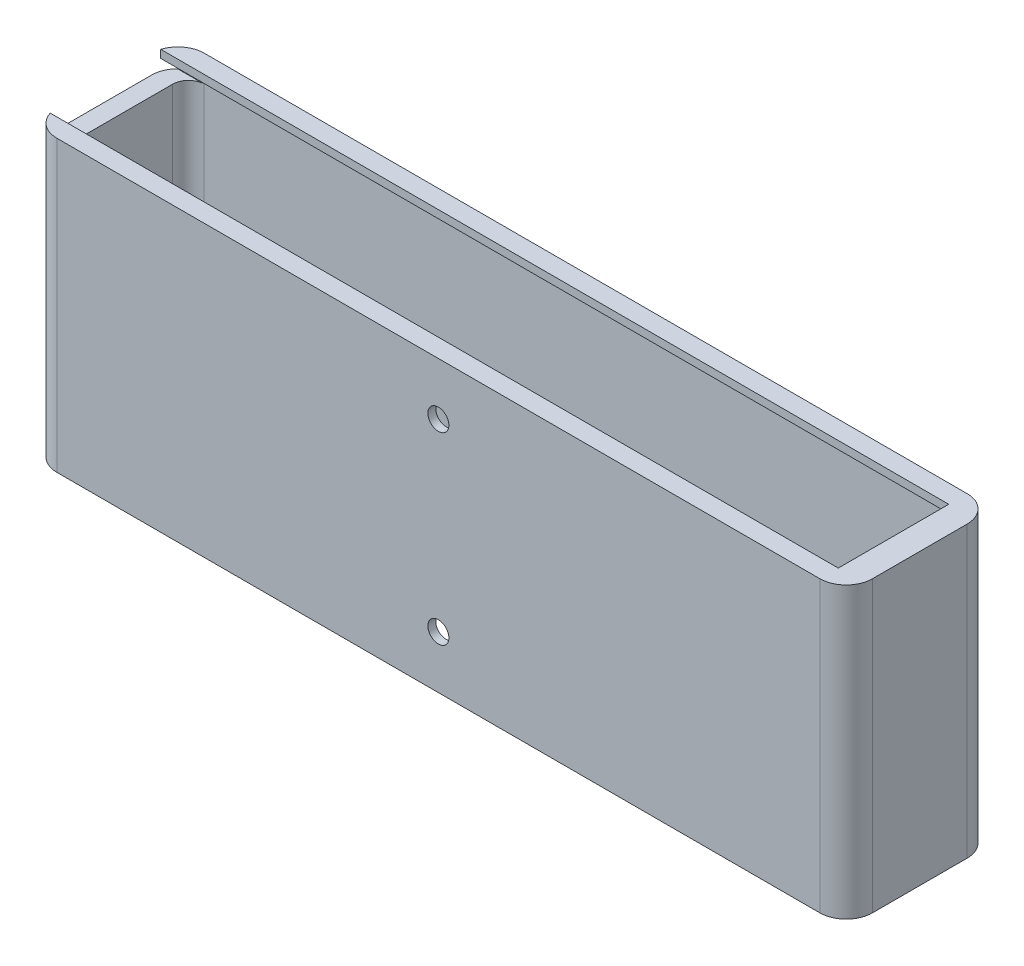
SolidWorks part; units mm, degrees
material "PVC 0.007 Plasticizado"
ref_plane "Plano frontal" through (0, 0, 0) normal (0, 0, 1) x (1, 0, 0)
ref_plane "Plano superior" through (0, 0, 0) normal (0, 1, 0) x (1, 0, 0)
ref_plane "Plano direito" through (0, 0, 0) normal (1, 0, 0) x (0, 0, -1)
sketch "Esboço1" plane through (0, 0, 0) normal (0, 0, 1) x (1, 0, 0)
  line L1 (-77.5, -27.5) -> (77.5, -27.5)
  line L2 (-77.5, -27.5) -> (-77.5, 27.5)
  line L3 (-77.5, 27.5) -> (77.5, 27.5)
  line L4 (77.5, -27.5) -> (77.5, 27.5)
  line L5 (-77.5, -27.5) -> (77.5, 27.5) construction
  line L6 (-77.5, 27.5) -> (77.5, -27.5) construction
  point P0 (0, 0)
  dimension "D1" = 55
  dimension "D2" = 155
extrude "Ressalto-extrusão1" add sketch "Esboço1" along normal blind 28
sketch "Esboço3" plane through (0, -27.5, 0) normal (0, -1, 0) x (1, 0, 0)
  line L0 (0, 0) -> (0, 28) construction
  line L1 (-77.5, 0) -> (77.5, 0) construction
  line L2 (-77.5, 28) -> (77.5, 28) construction
  line L4 (-74, 1.5) -> (74, 1.5)
  line L5 (-74, 1.5) -> (-74, 26.5)
  line L6 (-74, 26.5) -> (74, 26.5)
  line L7 (74, 1.5) -> (74, 26.5)
  line L8 (-74, 1.5) -> (74, 26.5) construction
  line L9 (-74, 26.5) -> (74, 1.5) construction
  point P6 (0, 14)
  dimension "D1" = 148
  dimension "D2" = 25
extrude "Corte-extrusão1" cut sketch "Esboço3" against normal through all
sketch "Esboço4" plane through (-77.5, 0, 0) normal (-1, 0, 0) x (0, 0, 1)
  line L0 (3.5, 27.5) -> (3.5, 26)
  line L2 (24.5, 27.5) -> (24.5, 26)
  line L3 (24.5, 26) -> (26.5, 26)
  line L4 (28, 27.5) -> (0, 27.5) construction
  line L5 (3.5, 26) -> (1.5, 26)
  line L6 (1.5, 26) -> (1.5, 23.9)
  line L7 (1.5, 23.9) -> (26.5, 23.9)
  line L8 (14, 23.9) -> (14, 27.5) construction
  line L9 (3.5, 27.5) -> (24.5, 27.5)
  line L10 (26.5, 26) -> (26.5, 23.9)
  dimension "D1" = 1.5
  dimension "D2" = 2.1
  dimension "D3" = 12.5
  dimension "D4" = 10.5
extrude "Corte-extrusão2" cut sketch "Esboço4" against normal up to next
sketch "Esboço6" plane through (-74, 0, 0) normal (1, 0, 0) x (0, 0, -1)
  line L0 (-3.5, 27.5) -> (-1.5, 27.5)
  line L1 (-1.5, 27.5) -> (-1.5, 26)
  line L2 (-1.5, 26) -> (-3.5, 26)
  line L3 (-3.5, 26) -> (-3.5, 27.5)
extrude "Ressalto-extrusão2" add sketch "Esboço6" along normal up to next
sketch "Esboço7" plane through (-74, 0, 0) normal (1, 0, 0) x (0, 0, -1)
  line L0 (-26.5, 27.5) -> (-24.5, 27.5)
  line L1 (-24.5, 27.5) -> (-24.5, 26)
  line L2 (-24.5, 26) -> (-26.5, 26)
  line L3 (-26.5, 26) -> (-26.5, 27.5)
extrude "Ressalto-extrusão3" add sketch "Esboço7" along normal up to next
sketch "Esboço9" plane through (74, 0, 0) normal (-1, 0, 0) x (0, 0, 1)
  line L0 (24.5, 27.5) -> (24.5, 26)
  line L1 (24.5, 26) -> (3.5, 26)
  line L2 (3.5, 26) -> (3.5, 27.5)
  line L3 (3.5, 27.5) -> (24.5, 27.5)
extrude "Ressalto-extrusão4" add sketch "Esboço9" along normal blind 1.5
fillet "Filete1" radius 5 4 edges at (-77.5, 0, 28) (-77.5, 0, 0) (77.5, 0, 0) (77.5, 0, 28)
fillet "Filete2" radius 3 4 edges at (-74, -1.8, 1.5) (-74, -1.8, 26.5) (74, -0.75, 26.5) (74, -0.75, 1.5)
sketch "Esboço12" plane through (0, -27.5, 0) normal (0, -1, 0) x (1, 0, 0)
  line L0 (74, 4.5) -> (74, 23.5) construction
  line L1 (-44.2797, 26.5) -> (-44.2797, 1.5) construction
  line L2 (74, 14) -> (-77.5, 14) construction
  line L3 (-77.5, 23) -> (-77.5, 5) construction
  line L4 (-21.3047, 26.5) -> (-17.5594, 26.5)
  line L5 (71, 26.5) -> (-76.0707, 26.5) construction
  line L7 (-71, 1.5) -> (71, 1.5) construction
  line L8 (-29.4196, 16.3438) -> (-21.3047, 26.5)
  line L11 (-29.4196, 16.3438) -> (-37.5344, 26.5)
  line L13 (-37.5344, 26.5) -> (-41.2797, 26.5)
  line L18 (-41.2797, 26.5) -> (-31.2922, 14)
  line L25 (-71, 26.5) -> (-71, 1.5) construction
  line L26 (-71, 26.5) -> (-61.0125, 14)
  line L27 (-41.2797, 1.5) -> (-31.2922, 14)
  line L28 (71, 1.5) -> (-76.0707, 1.5) construction
  line L29 (-51.025, 1.5) -> (-47.2797, 1.5)
  line L30 (-47.2797, 1.5) -> (-57.2672, 14)
  line L31 (71, 26.5) -> (-71, 26.5) construction
  line L32 (-67.2547, 26.5) -> (-71, 26.5)
  line L33 (-71, 1.5) -> (-61.0125, 14)
  line L34 (-51.025, 26.5) -> (-47.2797, 26.5)
  line L35 (-47.2797, 26.5) -> (-57.2672, 14)
  line L36 (-67.2547, 1.5) -> (-71, 1.5)
  line L37 (-59.1399, 16.3437) -> (-51.025, 26.5)
  line L38 (-59.1399, 16.3437) -> (-67.2547, 26.5)
  line L39 (-59.1399, 11.6562) -> (-67.2547, 1.5)
  line L40 (-59.1399, 11.6562) -> (-51.025, 1.5)
  line L41 (-37.5344, 1.5) -> (-41.2797, 1.5)
  line L42 (-29.4196, 11.6562) -> (-37.5344, 1.5)
  line L43 (-29.4196, 11.6562) -> (-21.3047, 1.5)
  line L44 (-21.3047, 1.5) -> (-17.5594, 1.5)
  line L45 (-17.5594, 1.5) -> (-27.5469, 14)
  line L46 (-17.5594, 26.5) -> (-27.5469, 14)
  line L47 (-14.5594, 26.5) -> (-14.5594, 1.5) construction
  line L48 (0.3007, 16.3438) -> (-7.8141, 26.5)
  line L49 (0.3007, 16.3438) -> (8.4156, 26.5)
  line L50 (8.4156, 26.5) -> (12.1609, 26.5)
  line L51 (12.1609, 26.5) -> (2.1734, 14)
  line L52 (12.1609, 1.5) -> (2.1734, 14)
  line L53 (8.4156, 1.5) -> (12.1609, 1.5)
  line L54 (0.3007, 11.6562) -> (8.4156, 1.5)
  line L55 (0.3007, 11.6562) -> (-7.8141, 1.5)
  line L56 (-7.8141, 1.5) -> (-11.5594, 1.5)
  line L57 (-11.5594, 1.5) -> (-1.5719, 14)
  line L58 (-11.5594, 26.5) -> (-1.5719, 14)
  line L59 (-7.8141, 26.5) -> (-11.5594, 26.5)
  line L60 (15.1609, 26.5) -> (15.1609, 1.5) construction
  line L61 (30.021, 16.3438) -> (21.9062, 26.5)
  line L62 (21.9062, 26.5) -> (18.1609, 26.5)
  line L63 (18.1609, 26.5) -> (28.1484, 14)
  line L64 (18.1609, 1.5) -> (28.1484, 14)
  line L65 (21.9062, 1.5) -> (18.1609, 1.5)
  line L66 (30.021, 11.6562) -> (21.9062, 1.5)
  line L67 (30.021, 11.6562) -> (38.1359, 1.5)
  line L68 (38.1359, 1.5) -> (41.8812, 1.5)
  line L69 (41.8812, 1.5) -> (31.8937, 14)
  line L70 (41.8812, 26.5) -> (31.8937, 14)
  line L71 (38.1359, 26.5) -> (41.8812, 26.5)
  line L72 (30.021, 16.3438) -> (38.1359, 26.5)
  line L73 (44.8812, 26.5) -> (44.8812, 1.5) construction
  line L74 (59.7413, 16.3438) -> (51.6265, 26.5)
  line L75 (51.6265, 26.5) -> (47.8812, 26.5)
  line L76 (47.8812, 26.5) -> (57.8687, 14)
  line L77 (47.8812, 1.5) -> (57.8687, 14)
  line L78 (51.6265, 1.5) -> (47.8812, 1.5)
  line L79 (59.7413, 11.6562) -> (51.6265, 1.5)
  line L80 (59.7413, 11.6562) -> (67.8562, 1.5)
  line L81 (67.8562, 1.5) -> (71.6015, 1.5)
  line L82 (71.6015, 1.5) -> (61.614, 14)
  line L83 (71.6015, 26.5) -> (61.614, 14)
  line L84 (67.8562, 26.5) -> (71.6015, 26.5)
  line L85 (59.7413, 16.3438) -> (67.8562, 26.5)
  dimension "D1" = 13
  dimension "D2" = 16
  dimension "D3" = 3
  dimension "D4" = 3
  dimension "D5" = 3
  dimension "D6" = 3
extrude "Ressalto-extrusão5" add sketch "Esboço12" against normal blind 1.5
sketch "Esboço15" plane through (0, 0, 28) normal (0, 0, 1) x (1, 0, 0)
  line L0 (0, 27.5) -> (0, -27.5) construction
  line L1 (72.5, 27.5) -> (-72.5, 27.5) construction
  line L2 (-72.5, -27.5) -> (72.5, -27.5) construction
  line L3 (72.5, 0) -> (-72.5, 0) construction
  line L4 (72.5, -27.5) -> (72.5, 27.5) construction
  line L5 (-72.5, 27.5) -> (-72.5, -27.5) construction
  circle A0 centre (0, 17.5) radius 2
  circle A1 centre (0, -17.5) radius 2
  dimension "D1" = 4
  dimension "D2" = 10
extrude "Corte-extrusão5" cut sketch "Esboço15" against normal up to next
